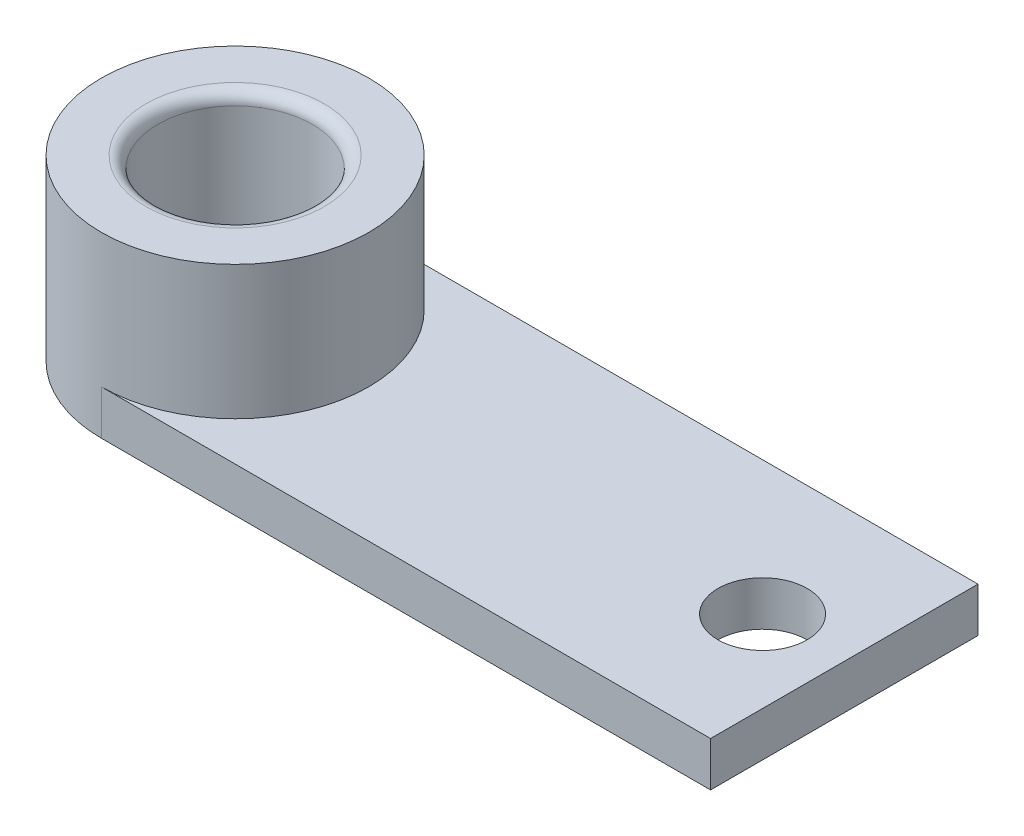
SolidWorks part; units mm, degrees
ref_plane "Front Plane" through (0, 0, 0) normal (0, 0, 1) x (1, 0, 0)
ref_plane "Top Plane" through (0, 0, 0) normal (0, 1, 0) x (1, 0, 0)
ref_plane "Right Plane" through (0, 0, 0) normal (1, 0, 0) x (0, 0, -1)
sketch "Sketch2" plane through (0, 0, 0) normal (0, 1, 0) x (1, 0, 0)
  line L0 (0, 0) -> (25, 0)
  line L1 (25, 0) -> (25, 9)
  line L2 (25, 9) -> (0, 9)
  line L3 (0, 9) -> (0, 0)
  line L4 (0, 4.5) -> (4.5, 4.5) construction
  line L5 (25, 4.5) -> (22.25, 4.5) construction
  dimension "D1" = 25
  dimension "D2" = 9
  dimension "D3" = 4.5
  dimension "D5" = 2.75
extrude "Boss-Extrude3" add sketch "Sketch2" along normal blind 6
sketch "Sketch3" plane through (0, 6, 0) normal (0, 1, 0) x (1, 0, 0)
  line L0 (0, 4.5) -> (4.5, 4.5) construction
  line L1 (0, 9) -> (0, 0) construction
  line L2 (25, 4.5) -> (22.25, 4.5) construction
  line L3 (25, 0) -> (25, 9) construction
  circle A0 centre (4.5, 4.5) radius 2.6
  circle A1 centre (22.25, 4.5) radius 1.75
  dimension "D3" = 5.2
  dimension "D4" = 3.5
  dimension "D1" = 4.5
  dimension "D2" = 2.75
extrude "Cut-Extrude1" cut sketch "Sketch3" against normal blind 5 contours A0
sketch "Sketch4" plane through (0, 6, 0) normal (0, 1, 0) x (1, 0, 0)
  line L0 (25, 4.5) -> (22.25, 4.5) construction
  line L1 (25, 0) -> (25, 9) construction
  circle A0 centre (22.25, 4.5) radius 1.5
  dimension "D2" = 3
  dimension "D1" = 2.75
extrude "Cut-Extrude2" cut sketch "Sketch4" against normal through all both and the other way through all
sketch "Sketch5" plane through (0, 6, 0) normal (0, 1, 0) x (1, 0, 0)
  line L0 (4.5, 9) -> (0, 9)
  line L1 (0, 9) -> (0, 4.5)
  line L2 (0, 4.5) -> (0, 0)
  line L3 (0, 0) -> (4.5, 0)
  line L4 (4.5, 0) -> (25, 0)
  line L5 (25, 0) -> (25, 9)
  line L6 (25, 9) -> (4.5, 9)
  circle A0 centre (4.5, 4.5) radius 4.5
  circle M9 centre (22.25, 4.5) radius 1.5
  line M12 (0, 0) -> (25, 0)
  line M13 (25, 0) -> (25, 9)
  line M14 (25, 9) -> (0, 9)
extrude "Cut-Extrude3" cut sketch "Sketch5" against normal blind 4.5 contours A0 M12 M13 M14 M9
sketch "Sketch6" plane through (0, 6, 0) normal (0, 1, 0) x (1, 0, 0)
  line L0 (4.5, 9) -> (0, 9)
  line L1 (0, 9) -> (0, 0)
  line L2 (0, 0) -> (4.5, 0)
  circle A0 centre (4.5, 4.5) radius 4.5
  line M2 (0, 0) -> (4.5, 0)
  line M4 (4.5, 9) -> (0, 9)
  line M5 (0, 9) -> (0, 0)
extrude "Cut-Extrude4" cut sketch "Sketch6" against normal through all contours A0 M4 M5 | A0 L1 M2
sketch "Sketch7" plane through (0, 6, 0) normal (0, 1, 0) x (1, 0, 0)
  circle A0 centre (4.5, 4.5) radius 2.8
  circle A2 centre (4.5, 4.5) radius 2.6
  dimension "D1" = 5.6
fillet "Fillet2" radius 0.4 1 edges at (4.5, 6, -1.9)
